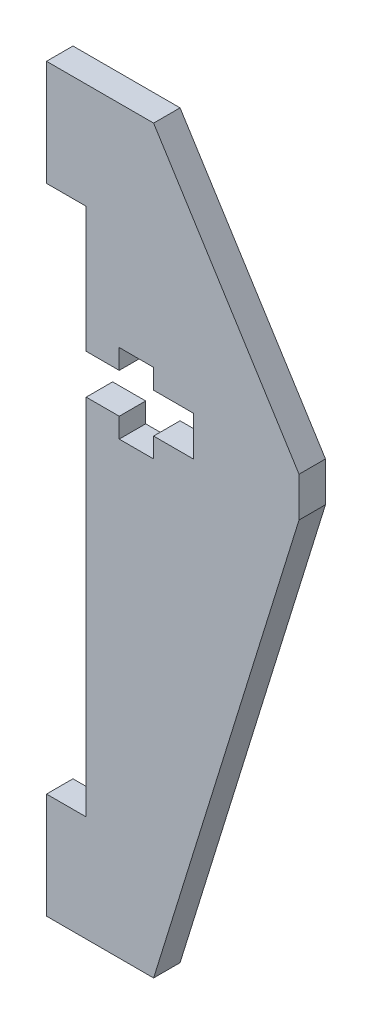
SolidWorks part; units mm, degrees
ref_plane "前视基准面" through (0, 0, 0) normal (0, 0, 1) x (1, 0, 0)
ref_plane "上视基准面" through (0, 0, 0) normal (0, 1, 0) x (1, 0, 0)
ref_plane "右视基准面" through (0, 0, 0) normal (1, 0, 0) x (0, 0, -1)
sketch "草图1" plane through (0, 0, 0) normal (0, 0, 1) x (1, 0, 0)
  line L0 (2.5, -1.5) -> (2.5, -3)
  line L1 (2.5, 1.5) -> (2.5, 3)
  line L2 (0, 1.5) -> (2.5, 1.5)
  line L3 (2.5, -3) -> (5.1, -3)
  line L4 (5.1, -3) -> (5.1, -1.5)
  line L5 (5.1, -1.5) -> (8.1, -1.5)
  line L6 (8.1, 1.5) -> (8.1, -1.5)
  line L7 (5.1, 1.5) -> (8.1, 1.5)
  line L8 (5.1, 3) -> (5.1, 1.5)
  line L9 (2.5, 3) -> (5.1, 3)
  line L10 (2.5, -1.5) -> (0, -1.5)
  line L11 (0, 1.5) -> (0, -1.5) construction
  line L12 (0, 0) -> (1.6273, 0) construction
  line L13 (0, 0) -> (0, 19) construction
  line L14 (0, 0) -> (0, -37) construction
  line L15 (0, 19) -> (-3, 19)
  line L16 (-3, 19) -> (-3, 11)
  line L17 (-3, 11) -> (0, 11)
  line L18 (0, 11) -> (0, 1.5)
  line L19 (0, -37) -> (-3, -37)
  line L20 (-3, -37) -> (-3, -29)
  line L21 (-3, -29) -> (0, -29)
  line L22 (0, -29) -> (0, -1.5)
  line L23 (8.1, 1.5) -> (16.1, 1.5) construction
  line L24 (0, 19) -> (5.1, 19)
  line L25 (5.1, 19) -> (16.1, 1.5)
  line L26 (16.1, 1.5) -> (16.1, -1.5)
  line L27 (16.1, -1.5) -> (5.1, -37)
  line L28 (5.1, -37) -> (0, -37)
  point P12 (8.1, 0)
extrude "凸台-拉伸1" add sketch "草图1" along normal blind 2 contours L25 L26 L27 L28 L19 L20 L21 L22 L10 L0 L3 L4 L5 L6 L7 L8 L9 L1 L2 L18 L17 L16 L15 L24
sketch "草图2" plane through (0, 0, 0) normal (-1, 0, 0) x (0, 0, 1)
  line L0 (2, -1.5) -> (0, 1.5)
  circle A0 centre (1, 0) radius 1.5
